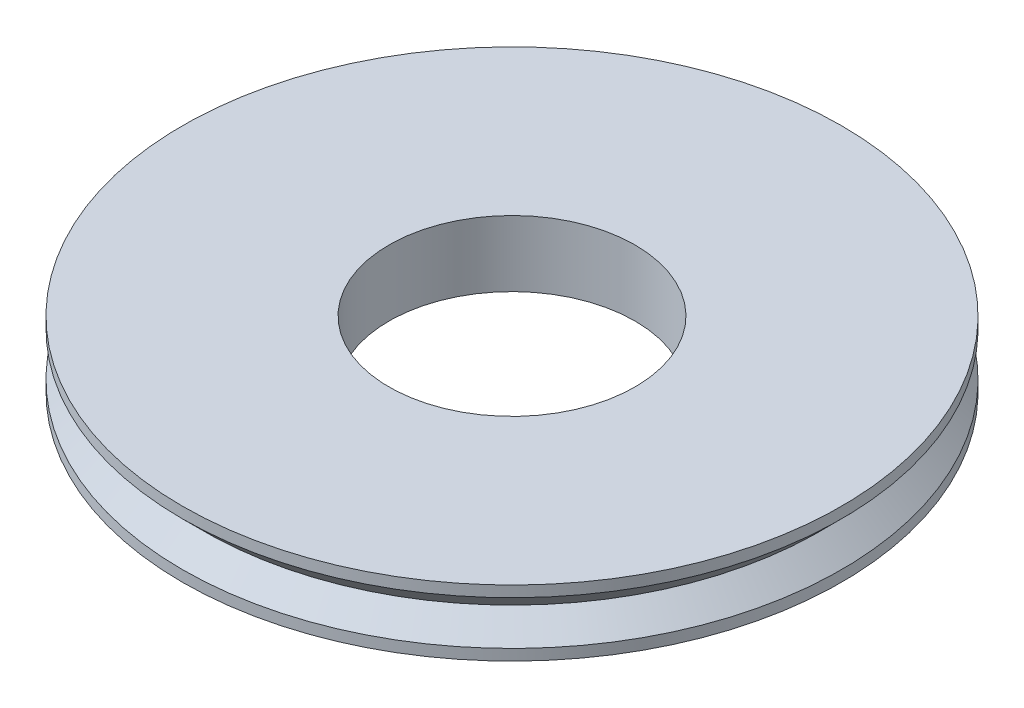
SolidWorks part; units mm, degrees
ref_plane "Front Plane" through (0, 0, 0) normal (0, 0, 1) x (1, 0, 0)
ref_plane "Top Plane" through (0, 0, 0) normal (0, 1, 0) x (1, 0, 0)
ref_plane "Right Plane" through (0, 0, 0) normal (1, 0, 0) x (0, 0, -1)
sketch "Sketch1" plane through (0, 0, 0) normal (0, 0, 1) x (1, 0, 0)
  line L0 (-5.6, 0) -> (-5.6, 3)
  line L1 (-5.6, 3) -> (-15, 3)
  line L2 (-15, 3) -> (-15, 2.5)
  line L3 (-15, 2.5) -> (-14, 1.5)
  line L4 (-14, 1.5) -> (-15, 0.5)
  line L5 (-15, 0.5) -> (-15, 0)
  line L6 (-5.6, 0) -> (-15, 0)
  line L7 (0, 0) -> (0, 9.0584) construction
  dimension "D1" = 5.6
  dimension "D2" = 0.5
  dimension "D3" = 0.5
  dimension "D4" = 1
  dimension "D5" = 1
  dimension "D6" = 1
  dimension "D7" = 15
  dimension "D8" = 0
revolve "Revolve1" add sketch "Sketch1" angle 360 about L7
